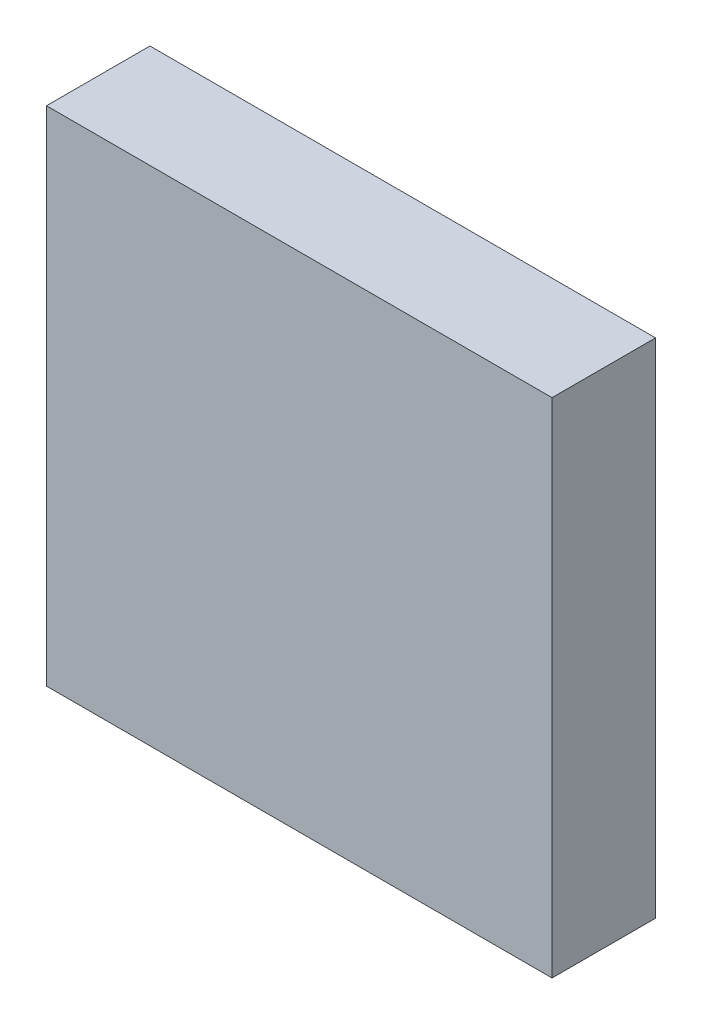
SolidWorks part; units mm, degrees
ref_plane "正面" through (0, 0, 0) normal (0, 0, 1) x (1, 0, 0)
ref_plane "平面" through (0, 0, 0) normal (0, 1, 0) x (1, 0, 0)
ref_plane "右側面" through (0, 0, 0) normal (1, 0, 0) x (0, 0, -1)
sketch "ｽｹｯﾁ1" plane through (0, 0, 0) normal (0, 1, 0) x (1, 0, 0)
  line L1 (-50.6309, 275.8634) -> (1659.3691, 275.8634)
  line L2 (-50.6309, 275.8634) -> (-50.6309, -74.1366)
  line L3 (-50.6309, -74.1366) -> (1659.3691, -74.1366)
  line L4 (1659.3691, 275.8634) -> (1659.3691, -74.1366)
  dimension "D1" = 1710
  dimension "D2" = 350
extrude "ﾎﾞｽ - 押し出し1" add sketch "ｽｹｯﾁ1" along normal blind 1700
